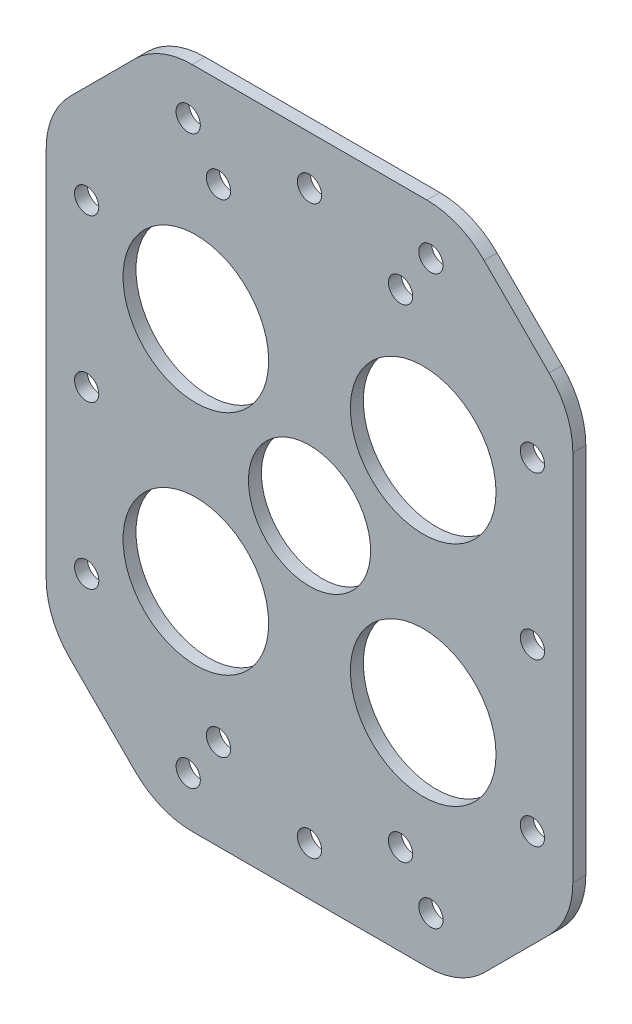
SolidWorks part; units mm, degrees
ref_plane "Ön Düzlem" through (0, 0, 0) normal (0, 0, 1) x (1, 0, 0)
ref_plane "Üst Düzlem" through (0, 0, 0) normal (0, 1, 0) x (1, 0, 0)
ref_plane "Sağ Düzlem" through (0, 0, 0) normal (1, 0, 0) x (0, 0, -1)
sketch "Çizim1" plane through (0, 0, 0) normal (0, 0, 1) x (1, 0, 0)
  line L0 (2.9289, -10.9711) -> (10.9711, -2.9289)
  line L1 (18.0421, 0) -> (47.0579, 0)
  line L2 (0, -18.0421) -> (0, -64.0579)
  line L3 (18.0421, -82.1) -> (47.0579, -82.1)
  line L4 (65.1, -18.0421) -> (65.1, -64.0579)
  line L5 (54.1289, -2.9289) -> (62.1711, -10.9711)
  line L6 (2.9289, -71.1289) -> (10.9711, -79.1711)
  line L7 (54.1289, -79.1711) -> (62.1711, -71.1289)
  line L8 (0, -41.05) -> (65.1, -41.05) construction
  arc A0 (2.9289, -71.1289) -> (0, -64.0579) centre (10, -64.0579) cw
  arc A1 (10.9711, -79.1711) -> (18.0421, -82.1) centre (18.0421, -72.1) ccw
  arc A2 (54.1289, -79.1711) -> (47.0579, -82.1) centre (47.0579, -72.1) cw
  arc A3 (62.1711, -71.1289) -> (65.1, -64.0579) centre (55.1, -64.0579) ccw
  arc A4 (62.1711, -10.9711) -> (65.1, -18.0421) centre (55.1, -18.0421) cw
  arc A5 (54.1289, -2.9289) -> (47.0579, 0) centre (47.0579, -10) ccw
  arc A6 (2.9289, -10.9711) -> (0, -18.0421) centre (10, -18.0421) ccw
  arc A7 (10.9711, -2.9289) -> (18.0421, 0) centre (18.0421, -10) cw
  circle A8 centre (18.5, -27) radius 9
  circle A9 centre (46.6, -27) radius 9
  circle A10 centre (18.5, -55.1) radius 9
  circle A11 centre (46.6, -55.1) radius 9
  circle A12 centre (32.55, -41.05) radius 7.55
  circle A13 centre (32.55, -6) radius 1.5
  circle A14 centre (47.55, -6) radius 1.5
  circle A15 centre (43.8, -11.2) radius 1.5
  circle A16 centre (17.55, -6) radius 1.5
  circle A17 centre (21.3, -11.2) radius 1.5
  circle A18 centre (5, -21.05) radius 1.5
  circle A19 centre (60.1, -21.05) radius 1.5
  circle A20 centre (5, -41.05) radius 1.5
  circle A21 centre (60.1, -41.05) radius 1.5
  circle A22 centre (60.1, -61.05) radius 1.5
  circle A23 centre (32.55, -76.1) radius 1.5
  circle A24 centre (47.55, -76.1) radius 1.5
  circle A25 centre (43.8, -70.9) radius 1.5
  circle A26 centre (21.3, -70.9) radius 1.5
  circle A27 centre (17.55, -76.1) radius 1.5
  circle A28 centre (5, -61.05) radius 1.5
  point P0 (0, 0)
  point P1 (65.1, -82.1)
  point P2 (0, -82.1)
  point P3 (65.1, 0)
  point P15 (0, -68.2)
  point P18 (13.9, -82.1)
  point P21 (51.2, -82.1)
  point P24 (65.1, -68.2)
  point P27 (65.1, -13.9)
  point P30 (51.2, 0)
  point P33 (0, -13.9)
  point P36 (13.9, 0)
  point P45 (32.55, 0)
  point P46 (0, -41.05)
  point P65 (65.1, -34.955)
  point P66 (65.1, -41.05)
  dimension "D3" = 10
  dimension "D4" = 18
  dimension "D9" = 18.5
  dimension "D10" = 27
  dimension "D11" = 18.5
  dimension "D12" = 27
  dimension "D13" = 15.1
  dimension "D14" = 3
  dimension "D15" = 6
  dimension "D16" = 15
  dimension "D17" = 15
  dimension "D18" = 11.2
  dimension "D19" = 22.5
  dimension "D20" = 11.25
  dimension "D21" = 5
  dimension "D22" = 5
  dimension "D23" = 20
  dimension "D1" = 65.1
  dimension "D2" = 82.1
extrude "Yükseklik-Ekstrüzyon1" add sketch "Çizim1" along normal blind 1.6
